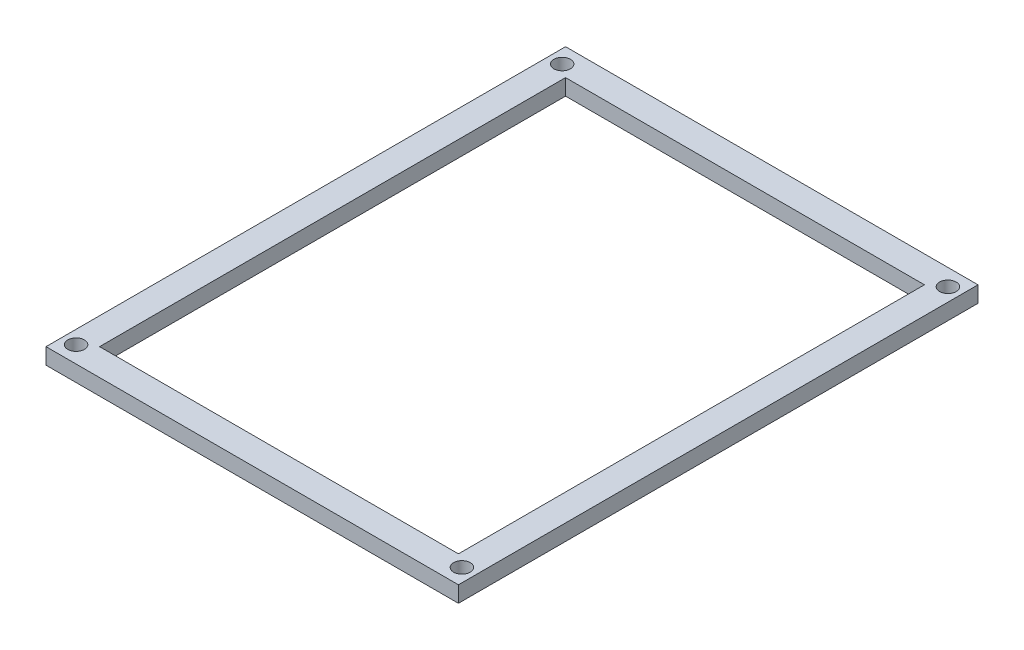
SolidWorks part; units mm, degrees
ref_plane "Front Plane" through (0, 0, 0) normal (0, 0, 1) x (1, 0, 0)
ref_plane "Top Plane" through (0, 0, 0) normal (0, 1, 0) x (1, 0, 0)
ref_plane "Right Plane" through (0, 0, 0) normal (1, 0, 0) x (0, 0, -1)
sketch "Sketch1" plane through (0, 0, 0) normal (0, 1, 0) x (1, 0, 0)
  line L0 (-5, -5) -> (72, -5)
  line L1 (0, 0) -> (67, 0)
  line L2 (0, 0) -> (0, 87)
  line L3 (0, 87) -> (67, 87)
  line L4 (67, 0) -> (67, 87)
  line L9 (72, -5) -> (72, 92)
  line L10 (-5, 92) -> (72, 92)
  line L11 (-5, -5) -> (-5, 92)
  line L18 (0, 87) -> (67, 0) construction
  circle A8 centre (69.5131, 88.8671) radius 1.55
  circle A9 centre (-2.5131, 88.8671) radius 1.55
  circle A10 centre (-2.5131, -1.8671) radius 1.55
  circle A11 centre (69.5131, -1.8671) radius 1.55
  dimension "D1" = 67
  dimension "D2" = 87
  dimension "D3" = 5
extrude "Boss-Extrude1" add sketch "Sketch1" along normal blind 3
